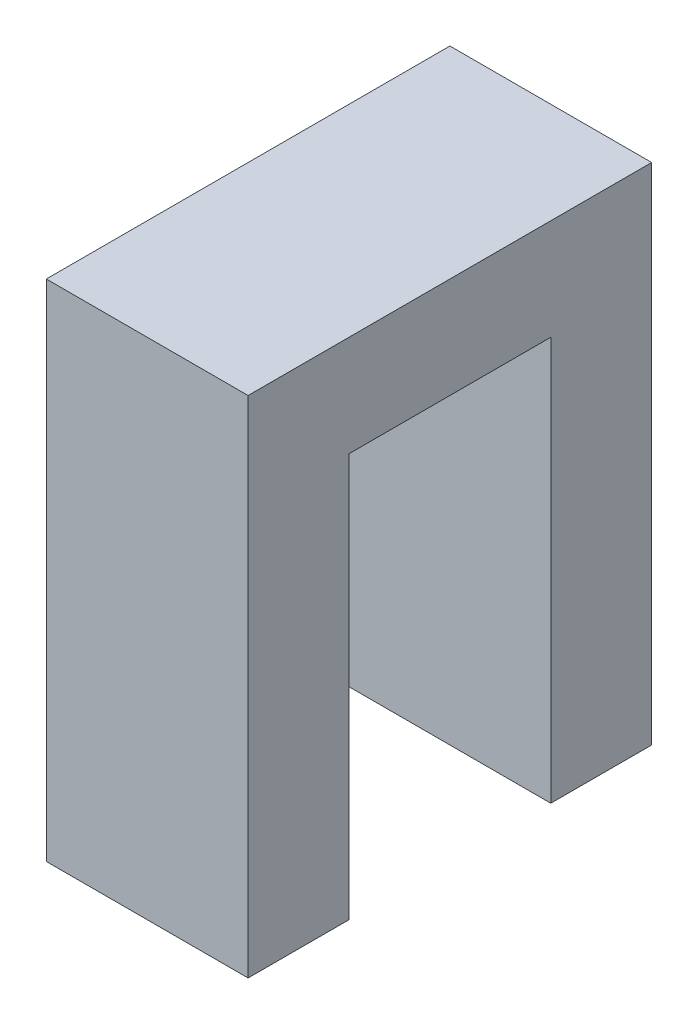
SolidWorks part; units mm, degrees
ref_plane "Alzado" through (0, 0, 0) normal (0, 0, 1) x (1, 0, 0)
ref_plane "Planta" through (0, 0, 0) normal (0, 1, 0) x (1, 0, 0)
ref_plane "Vista lateral" through (0, 0, 0) normal (1, 0, 0) x (0, 0, -1)
sketch "Croquis1" plane through (0, 0, 0) normal (0, 0, 1) x (1, 0, 0)
  line L1 (-20, -50) -> (20, -50)
  line L2 (-20, -50) -> (-20, 50)
  line L3 (-20, 50) -> (20, 50)
  line L4 (20, -50) -> (20, 50)
  line L5 (-20, -50) -> (20, 50) construction
  line L6 (-20, 50) -> (20, -50) construction
  point P0 (0, 0)
  dimension "D1" = 40
  dimension "D2" = 100
extrude "Saliente-Extruir1" add sketch "Croquis1" along normal mid plane 80
sketch "Croquis2" plane through (20, 0, 0) normal (1, 0, 0) x (0, 0, -1)
  line L0 (-40, -50) -> (40, -50) construction
  line L1 (-20, -50) -> (20, -50)
  line L2 (-20, -50) -> (-20, 30)
  line L3 (-20, 30) -> (20, 30)
  line L4 (20, -50) -> (20, 30)
  line L5 (-40, -50) -> (-40, 50) construction
  line L6 (40, -50) -> (40, 50) construction
  line L7 (-40, 50) -> (40, 50) construction
  dimension "D1" = 20
  dimension "D2" = 20
  dimension "D3" = 20
extrude "Cortar-Extruir1" cut sketch "Croquis2" against normal blind 110
